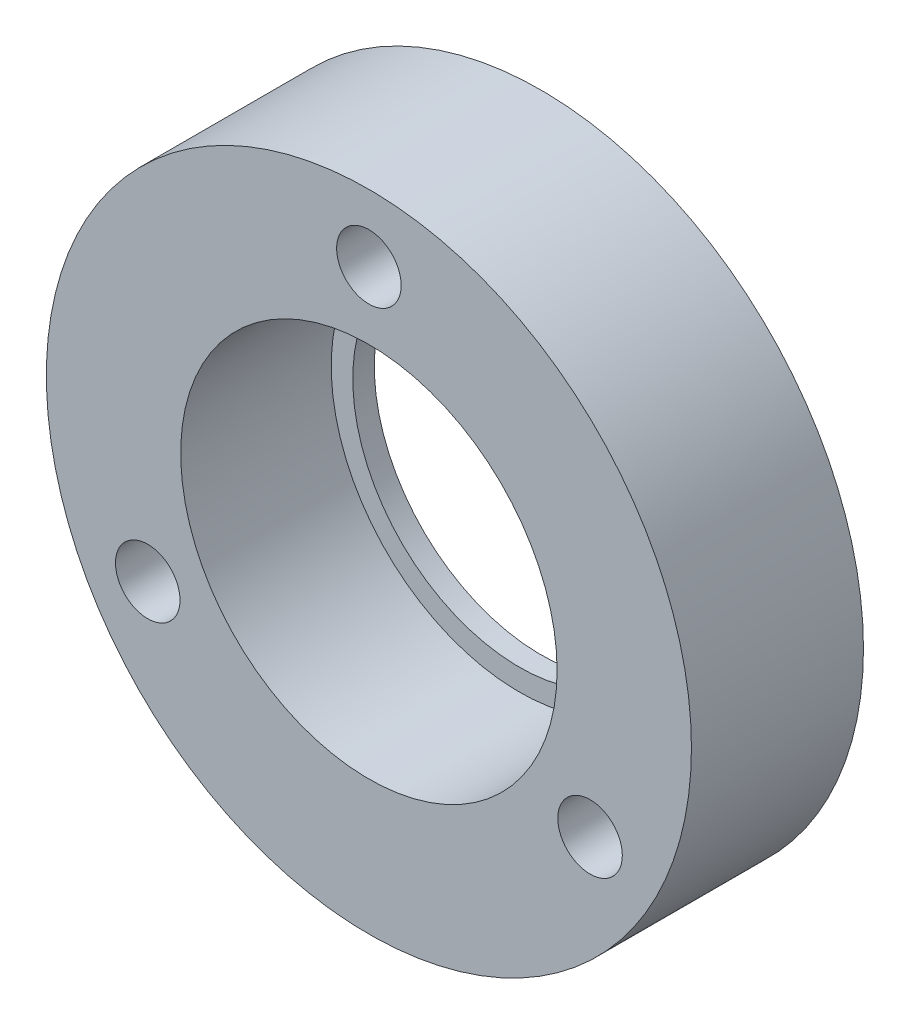
SolidWorks part; units mm, degrees
ref_plane "Front Plane" through (0, 0, 0) normal (0, 0, 1) x (1, 0, 0)
ref_plane "Top Plane" through (0, 0, 0) normal (0, 1, 0) x (1, 0, 0)
ref_plane "Right Plane" through (0, 0, 0) normal (1, 0, 0) x (0, 0, -1)
sketch "Sketch1" plane through (0, 0, 0) normal (0, 0, 1) x (1, 0, 0)
  circle A0 centre (0, 0) radius 30
extrude "Boss-Extrude1" add sketch "Sketch1" along normal blind 16
sketch "Sketch2" plane through (0, 0, 16) normal (0, 0, 1) x (1, 0, 0)
  circle A0 centre (0, 0) radius 17.505
extrude "Cut-Extrude1" cut sketch "Sketch2" against normal blind 14
sketch "Sketch4" plane through (0, 0, 2) normal (0, 0, 1) x (1, 0, 0)
  circle A0 centre (0, 0) radius 15.5
extrude "Cut-Extrude2" cut sketch "Sketch4" against normal through all
sketch "Sketch5" plane through (0, 0, 16) normal (0, 0, 1) x (1, 0, 0)
  circle A2 centre (0, 23.7525) radius 3
  circle A3 centre (20.5703, -11.8763) radius 3
  circle A4 centre (-20.5703, -11.8762) radius 3
  point P10 (0, 0)
  dimension "D1" = 3
extrude "Cut-Extrude3" cut sketch "Sketch5" against normal through all
